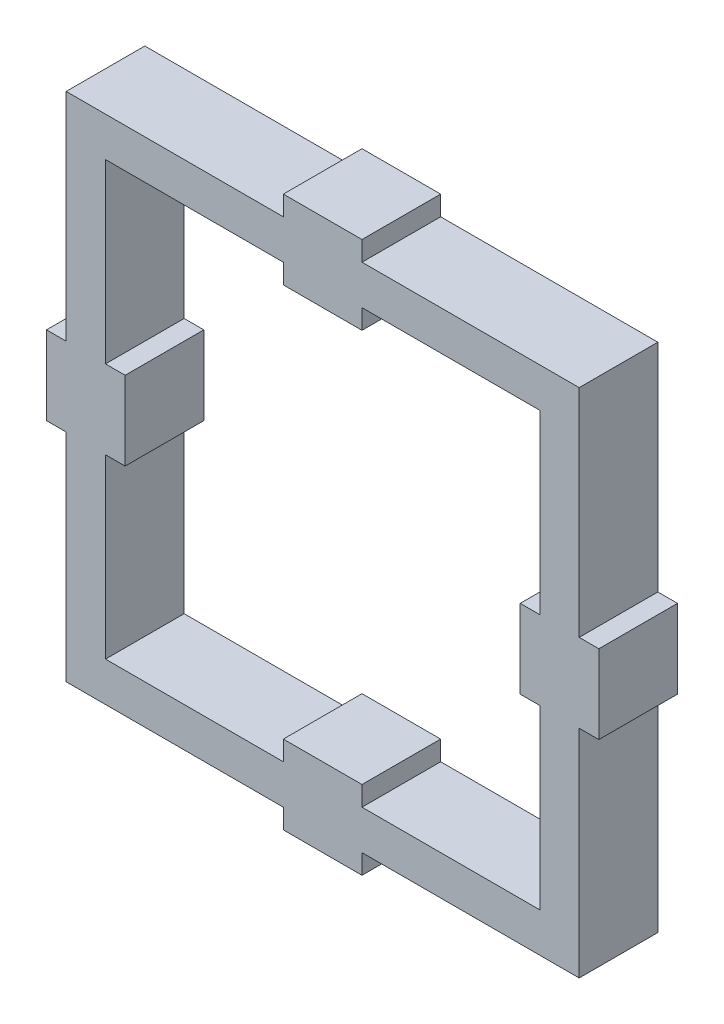
SolidWorks part; units mm, degrees
material "AISI 1020 Steel, Cold Rolled"
ref_plane "Front Plane" through (0, 0, 0) normal (0, 0, 1) x (1, 0, 0)
ref_plane "Top Plane" through (0, 0, 0) normal (0, 1, 0) x (1, 0, 0)
ref_plane "Right Plane" through (0, 0, 0) normal (1, 0, 0) x (0, 0, -1)
sketch "Sketch1" plane through (0, 0, 0) normal (0, 0, 1) x (1, 0, 0)
  line L0 (-15.1266, 1.2784) -> (15.1266, 1.2784) construction
  line L1 (-0.9174, 15.2784) -> (3.0826, 15.2784)
  line L2 (-0.9174, 15.2784) -> (-0.9174, 14.2784)
  line L3 (-0.9174, 11.2784) -> (3.0826, 11.2784)
  line L4 (3.0826, 15.2784) -> (3.0826, 14.2784)
  line L5 (-0.9174, 15.2784) -> (3.0826, 11.2784) construction
  line L6 (-0.9174, 11.2784) -> (3.0826, 15.2784) construction
  line L7 (-0.9174, -8.7216) -> (3.0826, -8.7216)
  line L8 (3.0826, -12.7216) -> (3.0826, -11.7216)
  line L9 (-0.9174, -12.7216) -> (3.0826, -12.7216)
  line L10 (-0.9174, -12.7216) -> (-0.9174, -11.7216)
  line L11 (1.0826, 4.8571) -> (1.0826, -1.2852) construction
  line L12 (-12.9614, 3.2784) -> (-11.9614, 3.2784)
  line L13 (-12.9614, 3.2784) -> (-12.9614, -0.7216)
  line L14 (-12.9614, -0.7216) -> (-11.9614, -0.7216)
  line L15 (-8.9614, 3.2784) -> (-8.9614, -0.7216)
  line L16 (-12.9614, 3.2784) -> (-8.9614, -0.7216) construction
  line L17 (-12.9614, -0.7216) -> (-8.9614, 3.2784) construction
  line L18 (15.1266, -0.7216) -> (14.1266, -0.7216)
  line L19 (11.1266, 3.2784) -> (11.1266, -0.7216)
  line L20 (15.1266, 3.2784) -> (14.1266, 3.2784)
  line L21 (15.1266, 3.2784) -> (15.1266, -0.7216)
  line L22 (3.0826, 14.2784) -> (14.1266, 14.2784)
  line L23 (-11.9614, 14.2784) -> (-11.9614, 3.2784)
  line L24 (-9.9614, 12.2784) -> (-9.9614, 3.2784)
  line L25 (3.0826, 12.2784) -> (12.1266, 12.2784)
  line L26 (-9.9614, 12.2784) -> (-0.9174, 12.2784)
  line L27 (-11.9614, 14.2784) -> (-0.9174, 14.2784)
  line L28 (-0.9174, -9.7216) -> (-0.9174, -8.7216)
  line L29 (3.0826, -11.7216) -> (14.1266, -11.7216)
  line L30 (-4.3313, -11.7216) -> (-0.9174, -11.7216)
  line L31 (-11.9614, -15.2769) -> (-11.8185, -15.2784)
  line L32 (-4.3313, -11.7216) -> (-11.9614, -11.7216)
  line L33 (14.1266, 14.2784) -> (14.1266, 3.2784)
  line L34 (15.1266, 3.2784) -> (15.1266, -0.7216)
  line L35 (3.0826, -9.7216) -> (12.1266, -9.7216)
  line L36 (12.1266, 3.2784) -> (11.1266, 3.2784)
  line L37 (12.1266, -0.7216) -> (11.1266, -0.7216)
  line L38 (12.1266, -0.7216) -> (12.1266, -9.7216)
  line L39 (14.1266, -0.7216) -> (14.1266, -11.7216)
  line L40 (-4.3313, -9.7216) -> (-0.9174, -9.7216)
  line L41 (-11.9614, -0.7216) -> (-11.9614, -11.7216)
  line L42 (-4.3313, -9.7216) -> (-9.9614, -9.7216)
  line L43 (3.0826, -9.7216) -> (3.0826, -8.7216)
  line L44 (-9.9614, -0.7216) -> (-8.9614, -0.7216)
  line L45 (-9.9614, 3.2784) -> (-8.9614, 3.2784)
  line L46 (-9.9614, -0.7216) -> (-9.9614, -9.7216)
  line L47 (-0.9174, 12.2784) -> (-0.9174, 11.2784)
  line L48 (3.0826, 12.2784) -> (3.0826, 11.2784)
  line L49 (12.1266, 12.2784) -> (12.1266, 3.2784)
  point P0 (1.0826, 13.2784)
  point P10 (-10.9614, 1.2784)
extrude "Boss-Extrude1" add sketch "Sketch1" along normal blind 4 contours L14 L41 L32 L30 L10 L9 L8 L29 L39 L18 L21 L20 L33 L22 L4 L1 L2 L27 L23 L12 L13 L25 L49 L36 L19 L37 L38 L35 L43 L7 L28 L40 L42 L46 L44 L15 L45 L24 L26 L47 L3 L48
sketch "Sketch3" plane through (-12.9614, 0, 0) normal (-1, 0, 0) x (0, 0, 1)
  line L4 (0, 3.2784) -> (0, -0.7216)
  line L5 (0, -0.7216) -> (4, -0.7216)
  line L6 (4, -0.7216) -> (4, 3.2784)
  line L7 (4, 3.2784) -> (0, 3.2784)
  line L8 (0, 3.2784) -> (0, -0.7216)
  line L9 (0, -0.7216) -> (4, -0.7216)
  line L10 (4, -0.7216) -> (4, 3.2784)
  line L11 (4, 3.2784) -> (0, 3.2784)
  circle A0 centre (2, 1.2784) radius 1
  dimension "D4" = 2
  dimension "D2" = 2
  dimension "D3" = 2
  dimension "D1" = 0
extrude "Cut-Extrude1" cut sketch "Sketch3" against normal blind 3 contours A0
